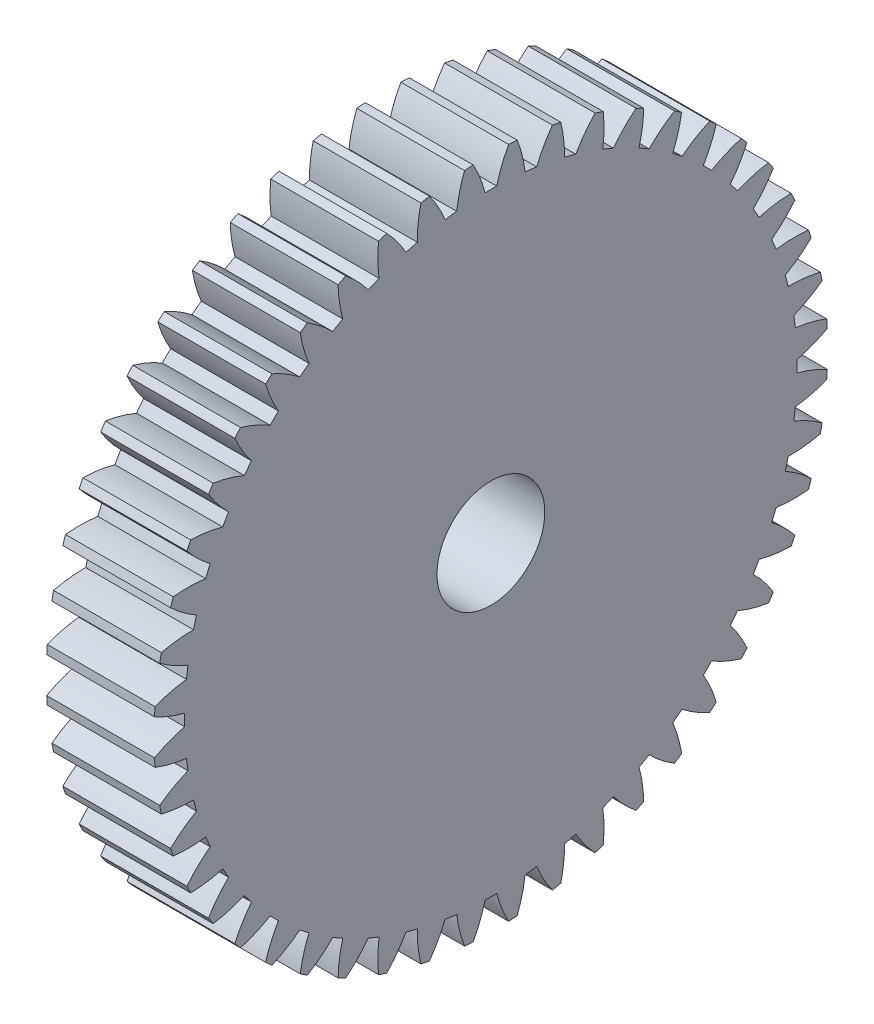
SolidWorks part; units mm, degrees
material "Delrin 2700 NC010, Low Viscosity Acetal Copolymer (SS)"
ref_plane "Plane1" through (0, 0, 0) normal (0, 0, 1) x (1, 0, 0)
ref_plane "Plane2" through (0, 0, 0) normal (0, 1, 0) x (1, 0, 0)
ref_plane "Plane3" through (0, 0, 0) normal (1, 0, 0) x (0, 0, -1)
other "Configuration Table"
sketch "HoldingSke" plane through (0, 0, 0) normal (0, 1, 0) x (1, 0, 0)
  line L0 (0, 0) -> (543.8694, -604.0281)
  line L1 (-15, 0) -> (100, 0) construction
  line L2 (0, 0) -> (-2.1039, 2.3779)
  line L3 (0, 0) -> (-11.863, 4.5341)
  line L4 (0, 0) -> (5.7786, 6.4178)
  line L5 (0, 0) -> (-11.8993, -4.4381)
  line L6 (0, 0) -> (-5.2639, -3.5516)
  line L7 (-2.1039, 2.3779) -> (0.6298, 14.7802)
  line L8 (-76.2, 54.61) -> (-69.596, 54.61)
  line L9 (-71.009, 38.7566) -> (-53.1078, 45.2721)
  line L10 (-76.2, 71.12) -> (104.1128, 71.12)
  line L11 (0, 0) -> (-6.35, 0)
  line L12 (-76.2, 101.6) -> (-76.1716, 101.6)
  line L13 (24.9733, 27.94) -> (52.9518, 28.4284)
  line L14 (24.9733, 27.94) -> (25.0241, 27.9398)
  line L15 (24.9733, 27.94) -> (100.4021, 29.52)
  circle A0 centre (0, 0) radius 3.175
  circle A1 centre (0, 0) radius 6.35
  circle A2 centre (0, 0) radius 6.35
  circle A3 centre (0, 0) radius 3.175
  dimension "Hub_dia" = 12.7
  dimension "Bore" = 6.35
  dimension "MBD" = 6.35
  dimension "Pitch" = 812.8
  dimension "Overall_len" = 12.7
  dimension "Thickness" = 6.35
  dimension "OAL" = 12.7001
  dimension "T_dim" = 6.604
  dimension "Ap" = 20
  dimension "H" = 19.05
  dimension "Pitch_radius" = 180.3128
  dimension "Backlash" = 0.0284
  dimension "Addendum_fac" = 1
  dimension "Dedendum_fac" = 1.2
  dimension "Clearance_fac" = 0.2
  dimension "Dedendum_add" = 0.0508
sketch "BasProSke" plane through (0, 0, 0) normal (0, 1, 0) x (1, 0, 0)
  line L0 (-10, 0) -> (60, 0) construction
  line L1 (0, 0) -> (0, 19.8438)
  line L2 (0, 0) -> (6.35, 0)
  line L3 (6.35, 0) -> (6.35, 19.8438)
  line L4 (6.35, 19.8438) -> (0, 19.8438)
  dimension "Thickness" = 6.35
revolve "Base-Revolve" add sketch "BasProSke" angle 360 about L0
sketch "TooCutSke" plane through (0, 0, 0) normal (1, 0, 0) x (0, 0, -1)
  line L1 (0, 0) -> (0, 107) construction
  line L2 (0, 0) -> (-0.6731, 19.0381) construction
  line L3 (0, 0) -> (-2.4907, 38.0012) construction
  line L4 (-0.6731, 19.0381) -> (-1.2454, 19.0006) construction
  arc A0 (0.3434, 18.0434) -> (-0.3434, 18.0434) centre (0, 0) ccw
  arc A1 (1.0583, 19.8409) -> (-1.0583, 19.8409) centre (0, 0) ccw
  circle A2 centre (0, 0) radius 19.05 construction
  circle A3 centre (0, 0) radius 17.9011 construction
  arc A4 (-0.3434, 18.0434) -> (-1.0583, 19.8409) centre (-7.7241, 16.149) ccw
  arc A5 (1.0583, 19.8409) -> (0.3434, 18.0434) centre (7.7241, 16.149) ccw
extrude "ToothCut" cut sketch "TooCutSke" along normal through all
fillet "Breaks" [suppressed] radius 0.0159
fillet "RootFillets" [suppressed] radius 0.2095
pattern_circular "TeethCuts" count 48 every 7.5 about axis through (-10, 0, 0) along (1, 0, 0) of "ToothCut", "RootFillets", "Breaks"
sketch "HubNeaOneSke" plane through (0, 0, 0) normal (-1, 0, 0) x (0, 0, 1)
  circle A0 centre (0, 0) radius 6.35
extrude "HubNearOne" add sketch "HubNeaOneSke" along normal blind 6.3501
sketch "HubNeaBotSke" plane through (0, 0, 0) normal (-1, 0, 0) x (0, 0, 1)
  circle A0 centre (0, 0) radius 6.35
extrude "HubNearBoth" [suppressed] add sketch "HubNeaBotSke" along normal blind 3.175
ref_plane "FarPln" through (6.35, 0, 0) normal (1, 0, 0) x (0, 0, -1)
sketch "HubFarSke" plane through (6.35, 0, 0) normal (1, 0, 0) x (0, 0, -1)
  circle A0 centre (0, 0) radius 6.35
extrude "HubFar" [suppressed] add sketch "HubFarSke" along normal blind 3.175
sketch "BorSke" plane through (0, 0, 0) normal (1, 0, 0) x (0, 0, -1)
  circle A0 centre (0, 0) radius 3.175
  dimension "Diameter" = 6.35
extrude "Bore" cut sketch "BorSke" along normal mid plane 25.4001
sketch "KeySke" plane through (0, 0, 0) normal (1, 0, 0) x (0, 0, -1)
  line L0 (-0.127, 0) -> (-0.127, 3.429)
  line L1 (-0.127, 3.429) -> (0.127, 3.429)
  line L2 (0.127, 3.429) -> (0.127, 0)
  line L3 (0, 0) -> (0, 34) construction
  line L4 (-0.127, 0) -> (0.127, 0)
  dimension "Offset" = 3.429
extrude "Keyway" [suppressed] cut sketch "KeySke" along normal mid plane 25.4001
pattern_circular "Keyway2" [suppressed] count 2 every 90 about axis through (-10, 0, 0) along (1, 0, 0)
equation "' \"Pitch@HoldingSke\" = 4"
equation "' \"Num_teeth@HoldingSke\" = 12"
equation "' \"Ap@HoldingSke\" =  20"
equation "' \"Ap@HoldingSke\" = 20"
equation "' \"Width@HoldingSke\" = 0.5"
equation "' \"Hub_dia@HoldingSke\"= 1"
equation "' \"Hub_dia@HoldingSke\" = 1"
equation "' \"Overall_len@HoldingSke\" = 1.0"
equation "' \"Bore@HoldingSke\" = 0.75"
equation "' \"T_dim@HoldingSke\" = 0.85"
equation "' \"Width@KeySke\" = 0.25"
equation "' \"Show_teeth@HoldingSke\" = 13"
equation "' \"Backlash@HoldingSke\" = 0.009"
equation "' \"Addendum_fac@HoldingSke\" = 1.0"
equation "' \"Dedendum_fac@HoldingSke\" = 1.25"
equation "' \"Dedendum_add@HoldingSke\" = 0.00005"
equation "' \"Clearance_fac@HoldingSke\" = 0.25"
equation "' \"Pitch@HoldingSke\" = 0.5"
equation "' \"Num_teeth@HoldingSke\" = 23"
equation "' \"Show_teeth@HoldingSke\" = 23"
equation "' \"Backlash@HoldingSke\" = 0.0375"
equation "\"Overcut_dia@TooCutSke\" = (\"Num_teeth@HoldingSke\" + 2 * \"Addendum_fac@HoldingSke\") / \"Pitch@HoldingSke\" + 0.002"
equation "\"Pitch_dia@TooCutSke\" = \"Num_teeth@HoldingSke\" / \"Pitch@HoldingSke\""
equation "\"Base_dia@TooCutSke\" = \"Num_teeth@HoldingSke\" / \"Pitch@HoldingSke\" * cos((\"Ap@HoldingSke\"  * 3.14159265 / 180))"
equation "\"Root_dia@TooCutSke\" = (\"Num_teeth@HoldingSke\" + 2) / \"Pitch@HoldingSke\" - 2 * (\"Addendum_fac@HoldingSke\" + \"Dedendum_fac@HoldingSke\") / \"Pitch@HoldingSke\" - \"Dedendum_add@HoldingSke\" * 2"
equation "\"Half_ang@TooCutSke\" = 180 / \"Num_teeth@HoldingSke\""
equation "\"Half_CT@TooCutSke\" = \"Num_teeth@HoldingSke\" / \"Pitch@HoldingSke\" * sin((3.14159265 / 2 / \"Num_teeth@HoldingSke\")) / 2 - 7 * \"Backlash@HoldingSke\" / 4"
equation "\"Flank_rad@TooCutSke\" = \"Num_teeth@HoldingSke\" / \"Pitch@HoldingSke\" / 5"
equation "\"Radius@RootFillets\" = \"Clearance_fac@HoldingSke\" / \"Pitch@HoldingSke\" + \"Dedendum_add@HoldingSke\""
equation "\"Break_rad@Breaks\" = 0.02 / \"Pitch@HoldingSke\""
equation "\"Thickness@HoldingSke\" = \"Width@HoldingSke\""
equation "\"OAL@HoldingSke\" = \"Thickness@HoldingSke\""
equation "\"MHD@HoldingSke\" = (\"Num_teeth@HoldingSke\" + 2) / \"Pitch@HoldingSke\" - 2 * (\"Addendum_fac@HoldingSke\" + \"Dedendum_fac@HoldingSke\")  / \"Pitch@HoldingSke\" - \"Dedendum_add@HoldingSke\" * 2"
equation "\"MBD@HoldingSke\" = (\"Num_teeth@HoldingSke\" + 2) / \"Pitch@HoldingSke\" - 2 * (\"Addendum_fac@HoldingSke\" + \"Dedendum_fac@HoldingSke\")  / \"Pitch@HoldingSke\" - \"Dedendum_add@HoldingSke\" * 2 - 0.002"
equation "\"MHD@HoldingSke\" = ((sgn( \"MHD@HoldingSke\" - \"Hub_dia@HoldingSke\" )-1)*( \"MHD@HoldingSke\" - \"Hub_dia@HoldingSke\" ))/-2+ \"Hub_dia@HoldingSke\""
equation "\"MBD@HoldingSke\" = ((sgn( \"MBD@HoldingSke\" - \"Bore@HoldingSke\" )-1)*( \"MBD@HoldingSke\" - \"Bore@HoldingSke\" ))/-2+ \"Bore@HoldingSke\""
equation "\"OAL@HoldingSke\" = ((sgn( \"OAL@HoldingSke\" - \"Overall_len@HoldingSke\" )+1)*( \"OAL@HoldingSke\" - \"Overall_len@HoldingSke\" ))/2 + \"Overall_len@HoldingSke\" + 0.000002"
equation "\"Num_teeth@TeethCuts\" = int( \"Show_teeth@HoldingSke\" ) + 1"
equation "\"Num_teeth@TeethCuts\" = ((sgn( \"Num_teeth@TeethCuts\" - \"Num_teeth@HoldingSke\" )-1)*( \"Num_teeth@TeethCuts\" - \"Num_teeth@HoldingSke\" ))/-2+ \"Num_teeth@HoldingSke\""
equation "\"Num_teeth@TeethCuts\" = ((sgn( \"Num_teeth@TeethCuts\" - 2.0)+1)*( \"Num_teeth@TeethCuts\" - 2.0))/2 +2.0"
equation "\"Angle@TeethCuts\" = 360.0 / \"Num_teeth@HoldingSke\""
equation "\"Diameter@BasProSke\" = (\"Num_teeth@HoldingSke\" + 2 * \"Addendum_fac@HoldingSke\") / \"Pitch@HoldingSke\""
equation "\"Thickness@BasProSke\"  = \"Thickness@HoldingSke\""
equation "' \"Fillet_rad@BasProSke\" =  \"Thickness@HoldingSke\" * 0.05"
equation "' \"Fillet_rad@BasProSke\" = \"Thickness@HoldingSke\" * 0.05"
equation "\"MHD@HoldingSke\" = ((sgn( \"MHD@HoldingSke\" - \"Root_dia@TooCutSke\" )-1)*( \"MHD@HoldingSke\" - \"Root_dia@TooCutSke\" ))/-2+ \"Root_dia@TooCutSke\""
equation "\"Diameter@HubNeaOneSke\" = \"MHD@HoldingSke\""
equation "\"Length@HubNearOne\" = \"OAL@HoldingSke\" - \"Thickness@BasProSke\""
equation "\"Diameter@HubNeaBotSke\" = \"MHD@HoldingSke\""
equation "\"Length@HubNearBoth\" = ( \"OAL@HoldingSke\" - \"Thickness@BasProSke\" ) / 2.0"
equation "\"Thickness@FarPln\" = \"Thickness@BasProSke\""
equation "\"Diameter@HubFarSke\" = \"MHD@HoldingSke\""
equation "\"Length@HubFar\" = ( \"OAL@HoldingSke\" - \"Thickness@BasProSke\" ) / 2.0"
equation "\"Diameter@BorSke\" = \"MBD@HoldingSke\""
equation "\"D1@Bore\" = \"OAL@HoldingSke\" * 2.0"
equation "\"D1@Keyway\" = \"OAL@HoldingSke\" * 2.0"
equation "\"Offset@KeySke\" = \"T_dim@HoldingSke\" - \"MBD@HoldingSke\" / 2.0"
